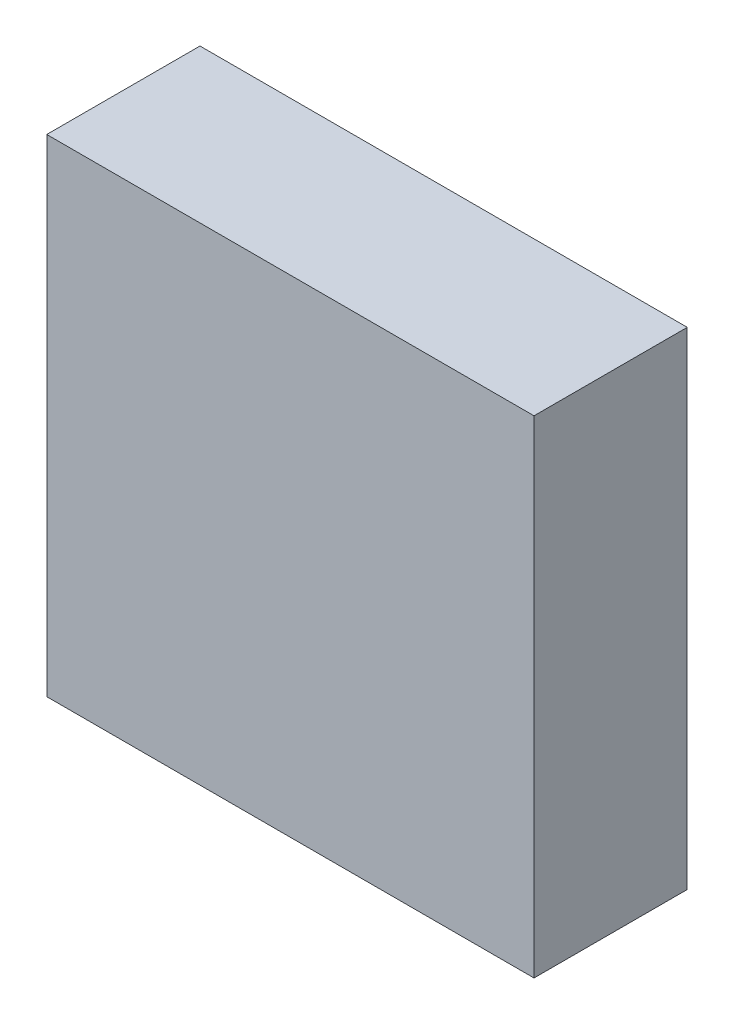
SolidWorks part; units mm, degrees
ref_plane "Front Plane" through (0, 0, 0) normal (0, 0, 1) x (1, 0, 0)
ref_plane "Top Plane" through (0, 0, 0) normal (0, 1, 0) x (1, 0, 0)
ref_plane "Right Plane" through (0, 0, 0) normal (1, 0, 0) x (0, 0, -1)
sketch "Sketch1" plane through (0, 0, 0) normal (0, 0, 1) x (1, 0, 0)
  line L0 (-1.59, 1.59) -> (1.59, 1.59)
  line L1 (1.59, 1.59) -> (1.59, -1.5875)
  line L2 (1.59, -1.5875) -> (-1.59, -1.5875)
  line L3 (-1.59, -1.5875) -> (-1.59, 1.59)
extrude "Component_Outline" add sketch "Sketch1" along normal blind 1 separate body
sketch3d "3DSketch1"
  line L0 (0, 0, 0) -> (1, 0, 0)
  line L1 (0, 0, 0) -> (0, 1, 0)
  line L2 (0, 0, 0) -> (0, 0, 1)
  point P0 (0, 0, 0)
